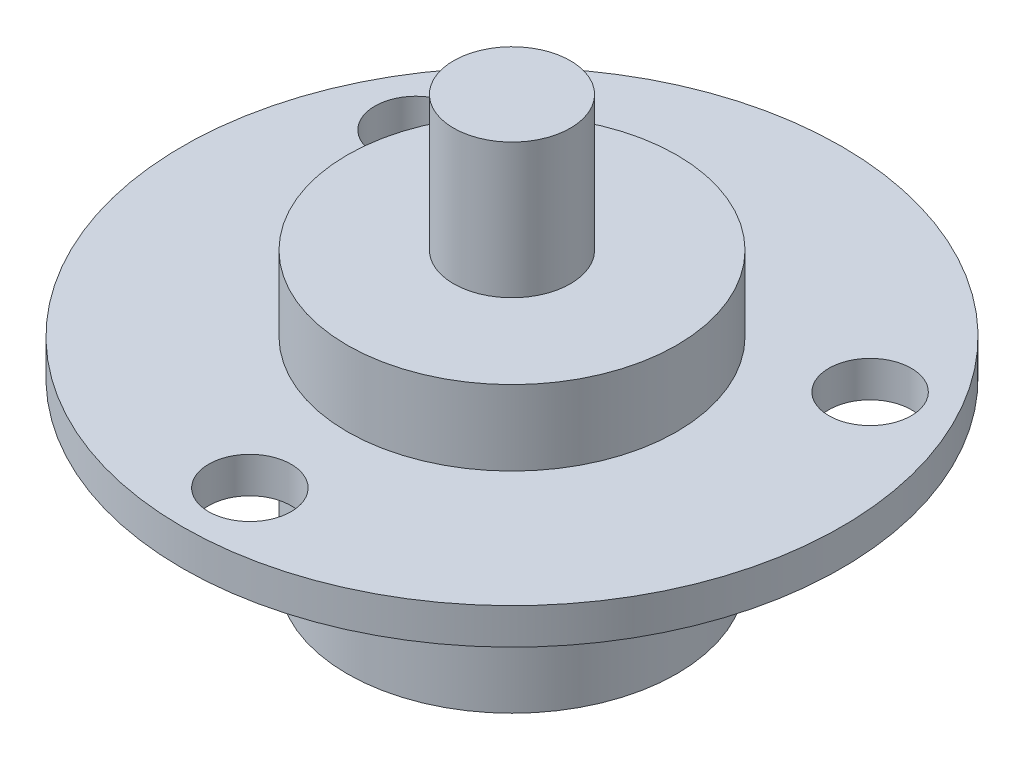
SolidWorks part; units mm, degrees
material "Nylon 6/10"
ref_plane "Front Plane" through (0, 0, 0) normal (0, 0, 1) x (1, 0, 0)
ref_plane "Top Plane" through (0, 0, 0) normal (0, 1, 0) x (1, 0, 0)
ref_plane "Right Plane" through (0, 0, 0) normal (1, 0, 0) x (0, 0, -1)
sketch "Sketch1" plane through (0, 0, 0) normal (0, 1, 0) x (1, 0, 0)
  circle A0 centre (0, 0) radius 11
  dimension "D1" = 22
extrude "Boss-Extrude1" add sketch "Sketch1" along normal blind 19
sketch "Sketch2" plane through (0, 19, 0) normal (0, 1, 0) x (1, 0, 0)
  circle A0 centre (0, 0) radius 3.9
  dimension "D1" = 7.8
extrude "Boss-Extrude2" add sketch "Sketch2" along normal blind 9
ref_plane "Plane1" through (0, 14, 0) normal (0, 1, 0) x (1, 0, 0)
sketch "Sketch3" plane through (0, 14, 0) normal (0, 1, 0) x (1, 0, 0)
  circle A0 centre (0, 0) radius 22
  circle A1 centre (0, 0) radius 17.5 construction
  circle A2 centre (0, -17.5) radius 2.75
  circle A3 centre (-15.1554, 8.75) radius 2.75
  circle A4 centre (15.1554, 8.75) radius 2.75
  point P12 (0, 0)
  dimension "D1" = 44
  dimension "D2" = 35
  dimension "D3" = 5.5
  dimension "D4" = 3
extrude "Boss-Extrude3" add sketch "Sketch3" against normal blind 2.4
